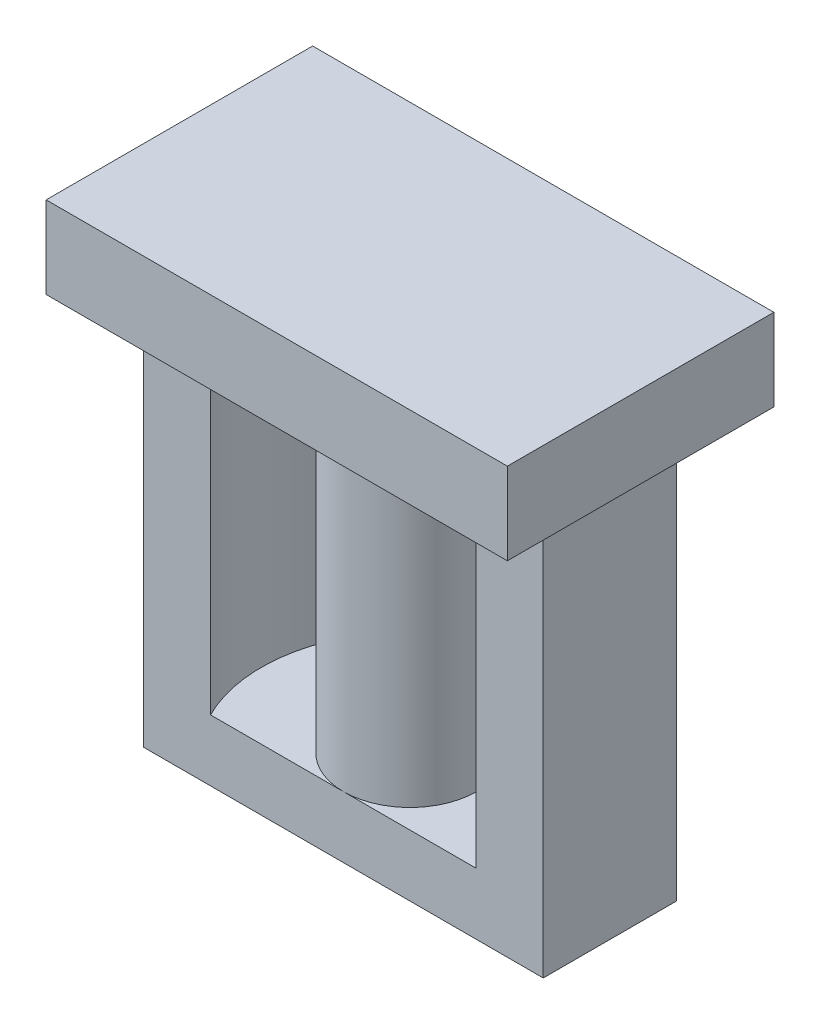
SolidWorks part; units mm, degrees
material "N87"
ref_plane "Спереди" through (0, 0, 0) normal (0, 0, 1) x (1, 0, 0)
ref_plane "Сверху" through (0, 0, 0) normal (0, 1, 0) x (1, 0, 0)
ref_plane "Справа" through (0, 0, 0) normal (1, 0, 0) x (0, 0, -1)
other "Configuration Table"
sketch "Эскиз1" plane through (0, 0, 0) normal (0, 1, 0) x (1, 0, 0)
  line L1 (0, 0) -> (39, 0)
  line L2 (0, 0) -> (0, 13)
  line L3 (0, 13) -> (39, 13)
  line L4 (39, 0) -> (39, 13)
  circle A0 centre (19.5, 6.5) radius 6.5
  circle A1 centre (19.5, 6.5) radius 14.5
  dimension "D3" = 29
  dimension "D4" = 13
  dimension "D1" = 39
  dimension "D2" = 13
  dimension "D5" = 6.5
  dimension "D6" = 19.5
extrude "Бобышка-Вытянуть1" add sketch "Эскиз1" along normal blind 14 contours A1 L3 L2 L1 | A0 | A1 L1 L4 L3
sketch "Эскиз2" plane through (0, 0, 0) normal (0, -1, 0) x (1, 0, 0)
  line L1 (0, 0) -> (39, 0)
  line L2 (0, 0) -> (0, -13)
  line L3 (0, -13) -> (39, -13)
  line L4 (39, 0) -> (39, -13)
extrude "Бобышка-Вытянуть2" add sketch "Эскиз2" along normal blind 6
sketch "Эскиз3" plane through (0, 14, 0) normal (0, 1, 0) x (1, 0, 0)
  line L0 (32.4615, 0) -> (39, 0) construction
  line L1 (39, 0) -> (39, 13) construction
  line L2 (39, 13) -> (32.4615, 13) construction
  line L3 (6.5385, 13) -> (0, 13) construction
  line L4 (0, 13) -> (0, 0) construction
  line L5 (0, 0) -> (6.5385, 0) construction
  line L6 (32.4615, 0) -> (39, 0)
  line L7 (39, 0) -> (39, 13)
  line L8 (39, 13) -> (32.4615, 13)
  line L9 (6.5385, 13) -> (0, 13)
  line L10 (0, 13) -> (0, 0)
  line L11 (0, 0) -> (6.5385, 0)
  arc A0 (32.4615, 0) -> (32.4615, 13) centre (19.5, 6.5) ccw construction
  arc A1 (6.5385, 13) -> (6.5385, 0) centre (19.5, 6.5) ccw construction
  circle A2 centre (19.5, 6.5) radius 6.5 construction
  arc A3 (32.4615, 0) -> (32.4615, 13) centre (19.5, 6.5) ccw
  arc A4 (6.5385, 13) -> (6.5385, 0) centre (19.5, 6.5) ccw
  circle A5 centre (19.5, 6.5) radius 6.5
extrude "Бобышка-Вытянуть3" add sketch "Эскиз3" along normal blind 14
sketch "Эскиз4" plane through (0, 28, 0) normal (0, 1, 0) x (1, 0, 0)
  line L1 (0, 13) -> (39, 13)
  line L2 (0, 13) -> (0, 0)
  line L3 (0, 0) -> (39, 0)
  line L4 (39, 13) -> (39, 0)
extrude "Бобышка-Вытянуть4" add sketch "Эскиз4" along normal blind 6
sketch "Эскиз5" plane through (0, 34, 0) normal (0, 1, 0) x (1, 0, 0)
  line L1 (-3, 19.5) -> (42, 19.5)
  line L2 (-3, 19.5) -> (-3, -6.5)
  line L3 (-3, -6.5) -> (42, -6.5)
  line L4 (42, 19.5) -> (42, -6.5)
  line L5 (0, 13) -> (0, 0) construction
  line L6 (39, 13) -> (0, 13) construction
  dimension "D1" = 26
  dimension "D2" = 45
  dimension "D3" = 3
  dimension "D4" = 6.5
extrude "Бобышка-Вытянуть5" add sketch "Эскиз5" along normal blind 8 contours L1 L4 L3 L2
